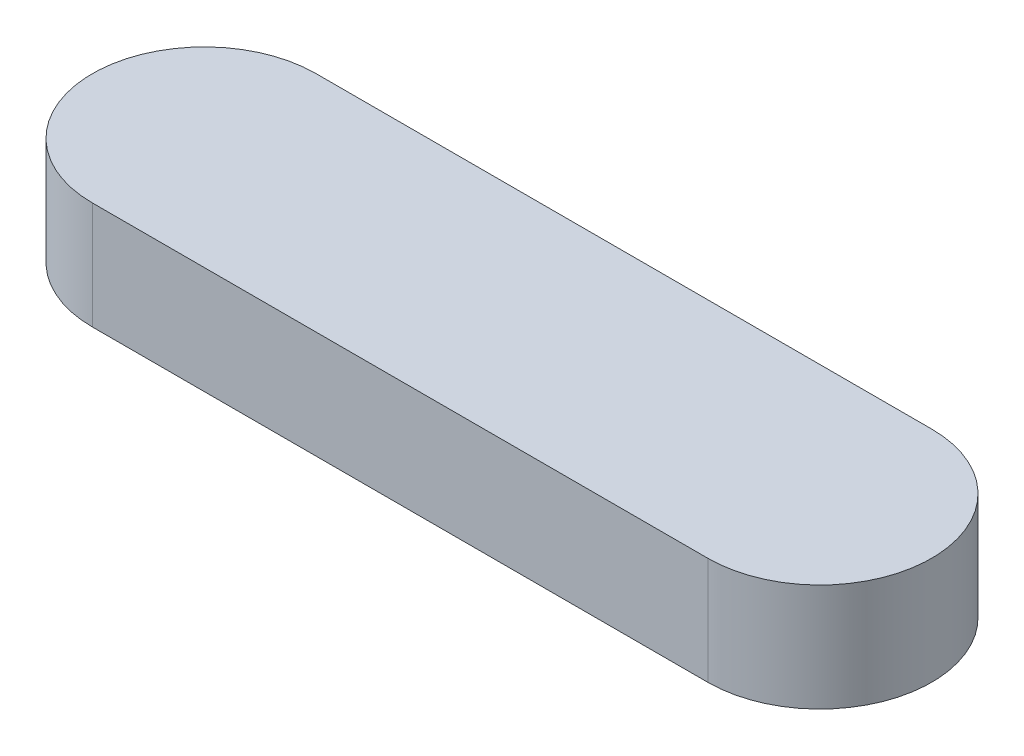
SolidWorks part; units mm, degrees
ref_plane "Front Plane" through (0, 0, 0) normal (0, 0, 1) x (1, 0, 0)
ref_plane "Top Plane" through (0, 0, 0) normal (0, 1, 0) x (1, 0, 0)
ref_plane "Right Plane" through (0, 0, 0) normal (1, 0, 0) x (0, 0, -1)
sketch "Sketch1" plane through (0, 0, 0) normal (0, 1, 0) x (1, 0, 0)
  line L0 (11, 0) -> (-11, 0) construction
  line L5 (11, -4) -> (-11, -4)
  line L6 (11, 4) -> (-11, 4)
  arc A0 (11, -4) -> (11, 4) centre (11, 0) ccw
  arc A1 (-11, 4) -> (-11, -4) centre (-11, 0) ccw
  point P2 (0, 0)
  dimension "D1" = 30
  dimension "D2" = 8
extrude "Boss-Extrude1" add sketch "Sketch1" along normal blind 3.84
